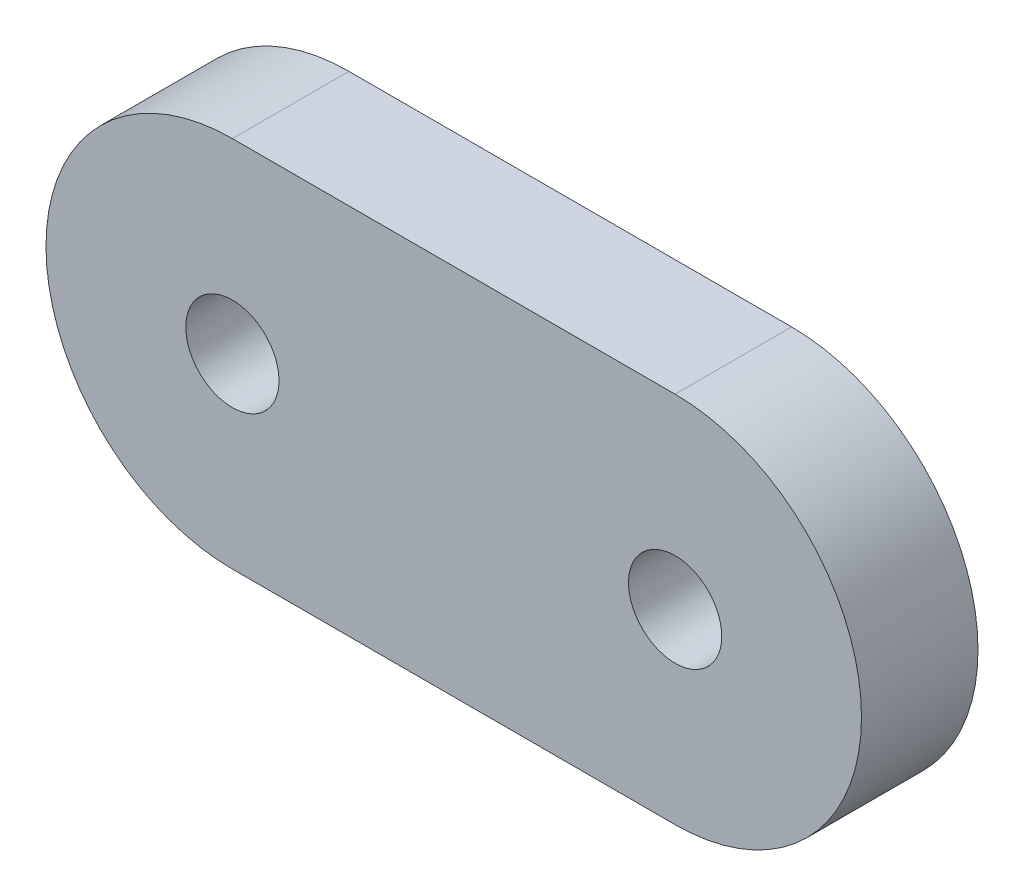
SolidWorks part; units mm, degrees
ref_plane "Front Plane" through (0, 0, 0) normal (0, 0, 1) x (1, 0, 0)
ref_plane "Top Plane" through (0, 0, 0) normal (0, 1, 0) x (1, 0, 0)
ref_plane "Right Plane" through (0, 0, 0) normal (1, 0, 0) x (0, 0, -1)
sketch "Sketch1" plane through (0, 0, 0) normal (0, 0, 1) x (1, 0, 0)
  line L0 (0, 0) -> (24.13, 0) construction
  line L1 (0, 10.16) -> (24.13, 10.16)
  line L2 (0, -10.16) -> (24.13, -10.16)
  line L3 (2.54, 0) -> (21.59, 0) construction
  arc A0 (0, 10.16) -> (0, -10.16) centre (0, 0) ccw
  arc A1 (24.13, -10.16) -> (24.13, 10.16) centre (24.13, 0) ccw
  circle A2 centre (0, 0) radius 2.54
  circle A3 centre (24.13, 0) radius 2.54
  point P3 (12.065, 0)
  dimension "D2" = 5.08
  dimension "D3" = 5.08
  dimension "D1" = 19.05
  dimension "D4" = 20.32
extrude "Boss-Extrude1" add sketch "Sketch1" along normal blind 6.35
equation "\"distance-between-holes\"= .75in"
equation "\"clamp-height\"= .8in"
equation "\"clamp-width\"= 1.5in"
equation "\"hole-diameter\"= .2in"
equation "\"material-thickness\"= .25in"
equation "\"D1@Boss-Extrude1\"=\"material-thickness\""
equation "\"D1@Sketch1\"=\"distance-between-holes\""
equation "\"D2@Sketch1\"=\"hole-diameter\""
equation "\"D3@Sketch1\"=\"hole-diameter\""
equation "\"D4@Sketch1\"=\"clamp-height\""
